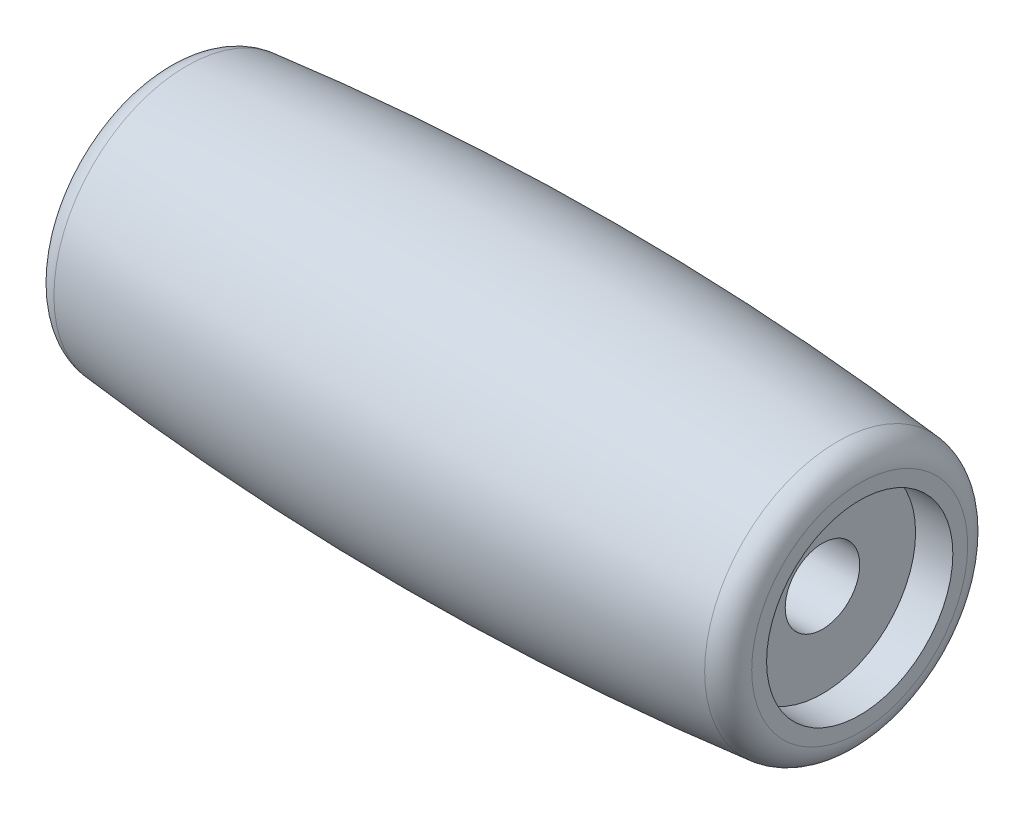
SolidWorks part; units mm, degrees
ref_plane "Front Plane" through (0, 0, 0) normal (0, 0, 1) x (1, 0, 0)
ref_plane "Top Plane" through (0, 0, 0) normal (0, 1, 0) x (1, 0, 0)
ref_plane "Right Plane" through (0, 0, 0) normal (1, 0, 0) x (0, 0, -1)
sketch "Sketch1" plane through (0, 0, 0) normal (0, 0, 1) x (1, 0, 0)
  line L0 (0, 0) -> (0, 6) construction
  line L1 (0, 0) -> (13.4995, 0) construction
  line L2 (-12.5, 1.5) -> (12.5, 1.5)
  line L3 (12.5, 1.5) -> (12.5, 3.75)
  line L4 (12.5, 3.75) -> (14, 3.75)
  line L5 (14, 3.75) -> (14, 4.3486)
  line L6 (-14, 3.75) -> (-14, 4.3486)
  line L7 (-12.5, 3.75) -> (-14, 3.75)
  line L8 (-12.5, 1.5) -> (-12.5, 3.75)
  arc A0 (-13.1, 5.3436) -> (13.1, 5.3436) centre (0, -125.0417) cw
  arc A1 (14, 4.3486) -> (13.1, 5.3436) centre (13, 4.3486) ccw
  arc A2 (-14, 4.3486) -> (-13.1, 5.3436) centre (-13, 4.3486) cw
  point P13 (0, 1.5)
  point P16 (14, 5.25)
  point P19 (-14, 5.25)
  dimension "D7" = 1
  dimension "D1" = 1.5
  dimension "D2" = 3.75
  dimension "D3" = 1.5
  dimension "D4" = 1.5
  dimension "D5" = 14
  dimension "D6" = 6
revolve "Revolve1" add sketch "Sketch1" angle 360 about L1
